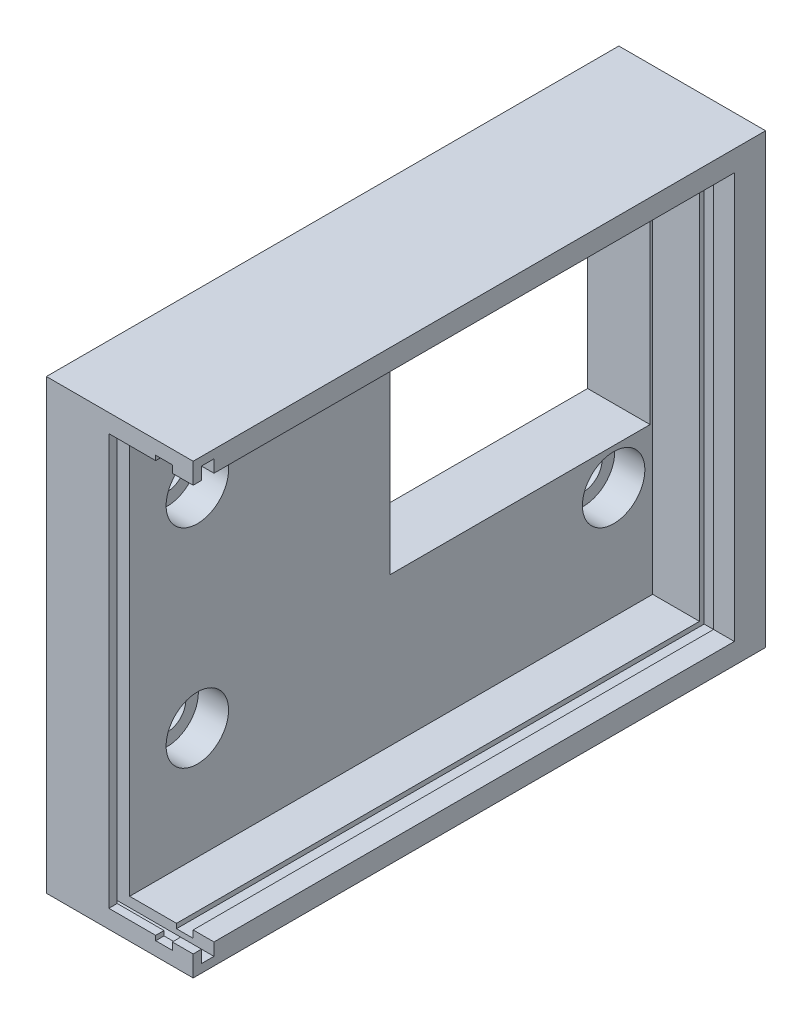
SolidWorks part; units mm, degrees
ref_plane "Front Plane" through (0, 0, 0) normal (1, 0, 0) x (0, 1, 0)
ref_plane "Top Plane" through (0, 0, 0) normal (0, 0, 1) x (0, 1, 0)
ref_plane "Right Plane" through (0, 0, 0) normal (0, 1, 0) x (-1, 0, 0)
sketch "Sketch1" plane through (0, 0, 0) normal (1, 0, 0) x (0, 1, 0)
  line L14 (-11.7365, -20.1625) -> (-11.7365, 19.8375) construction
  line L15 (-24.2365, 28.3375) -> (-24.2365, -26.6625)
  line L16 (-24.2365, 28.3375) -> (18.7635, 28.3375)
  line L17 (-24.2365, -26.6625) -> (18.7635, -26.6625)
  line L18 (18.7635, -26.6625) -> (18.7635, 28.3375)
  circle A0 centre (-11.7365, -20.1625) radius 1.8
  circle A1 centre (-11.7365, 19.8375) radius 1.8
  circle A2 centre (8.2635, 19.8375) radius 1.8
  dimension "D7" = 3.6
  dimension "D8" = 3.6
  dimension "D9" = 3.6
  dimension "D1" = 6.5
  dimension "D2" = 43
  dimension "D3" = 12.5
  dimension "D4" = 40
  dimension "D5" = 55
  dimension "D6" = 20
  dimension "D10" = 46.5
extrude "Boss-Extrude1" add sketch "Sketch1" along normal blind 6
sketch "Sketch3" plane through (6, 0, 0) normal (1, 0, 0) x (0, 1, 0)
  line L0 (-24.2365, 28.3375) -> (18.7635, -26.6625) construction
  line L5 (18.7635, -26.6625) -> (18.7635, 28.3375) construction
  line L6 (18.7635, 28.3375) -> (-24.2365, -26.6625) construction
  line L7 (-22.4865, 25.5875) -> (-22.4865, 28.3375)
  line L15 (-22.4865, 25.5875) -> (-22.4865, -23.9125)
  line L16 (-22.4865, -23.9125) -> (17.0135, -23.9125)
  line L19 (17.0135, 25.5875) -> (17.0135, -23.9125)
  line L20 (-22.4865, 25.5875) -> (17.0135, -23.9125) construction
  line L21 (-22.4865, -23.9125) -> (17.0135, 25.5875) construction
  line L22 (-24.2365, 28.3375) -> (-22.4865, 28.3375)
  line L23 (-24.2365, 28.3375) -> (-24.2365, -26.6625)
  line L24 (-24.2365, -26.6625) -> (18.7635, -26.6625)
  line L25 (18.7635, 28.3375) -> (18.7635, -26.6625)
  line L26 (-24.2365, 28.3375) -> (18.7635, -26.6625) construction
  line L27 (-24.2365, -26.6625) -> (18.7635, 28.3375) construction
  line L28 (17.0135, 25.5875) -> (17.0135, 28.3375)
  line L29 (17.0135, 28.3375) -> (18.7635, 28.3375)
  point P2 (-2.7365, 0.8375)
  point P9 (-2.7365, 0.8375)
  dimension "D1" = 49.5
  dimension "D2" = 39.5
extrude "Boss-Extrude2" add sketch "Sketch3" along normal blind 4.5
sketch "Sketch5" plane through (10.5, 0, 0) normal (1, 0, 0) x (0, 1, 0)
  line L0 (-24.2365, 28.3375) -> (18.7635, -26.6625) construction
  line L1 (18.7635, -26.6625) -> (18.7635, 28.3375) construction
  line L7 (18.7635, 28.3375) -> (-24.2365, -26.6625) construction
  line L8 (-22.9365, 26.0375) -> (-22.9365, 28.3375)
  line L14 (-22.9365, 26.0375) -> (-22.9365, -24.3625)
  line L18 (-22.9365, -24.3625) -> (17.4635, -24.3625)
  line L19 (17.4635, 26.0375) -> (17.4635, -24.3625)
  line L20 (-22.9365, 26.0375) -> (17.4635, -24.3625) construction
  line L21 (-22.9365, -24.3625) -> (17.4635, 26.0375) construction
  line L22 (-24.2365, 28.3375) -> (-22.9365, 28.3375)
  line L23 (-24.2365, 28.3375) -> (-24.2365, -26.6625)
  line L24 (-24.2365, -26.6625) -> (18.7635, -26.6625)
  line L25 (18.7635, 28.3375) -> (18.7635, -26.6625)
  line L26 (-24.2365, 28.3375) -> (18.7635, -26.6625) construction
  line L27 (-24.2365, -26.6625) -> (18.7635, 28.3375) construction
  line L28 (17.4635, 26.0375) -> (17.4635, 28.3375)
  line L29 (17.4635, 28.3375) -> (18.7635, 28.3375)
  point P4 (-2.7365, 0.8375)
  point P13 (-2.7365, 0.8375)
  dimension "D1" = 50.4
  dimension "D2" = 40.4
extrude "Boss-Extrude3" add sketch "Sketch5" along normal blind 1.6 contours L14 L18 L19 L28 L29 L25 L24 L23 L22 L8
sketch "Sketch6" plane through (12.1, 0, 0) normal (1, 0, 0) x (0, 1, 0)
  line L4 (-24.2365, 28.3375) -> (18.7635, -26.6625) construction
  line L5 (18.7635, -26.6625) -> (18.7635, 28.3375) construction
  line L11 (18.7635, 28.3375) -> (-24.2365, -26.6625) construction
  line L12 (-22.2365, 25.3375) -> (-22.2365, 28.3375)
  line L16 (-22.2365, 25.3375) -> (-22.2365, -23.6625)
  line L17 (-22.2365, -23.6625) -> (16.7635, -23.6625)
  line L18 (16.7635, 25.3375) -> (16.7635, -23.6625)
  line L19 (-22.2365, 25.3375) -> (16.7635, -23.6625) construction
  line L20 (-22.2365, -23.6625) -> (16.7635, 25.3375) construction
  line L21 (-24.2365, 28.3375) -> (-22.2365, 28.3375)
  line L22 (-24.2365, 28.3375) -> (-24.2365, -26.6625)
  line L23 (-24.2365, -26.6625) -> (18.7635, -26.6625)
  line L24 (18.7635, 28.3375) -> (18.7635, -26.6625)
  line L25 (-24.2365, 28.3375) -> (18.7635, -26.6625) construction
  line L26 (-24.2365, -26.6625) -> (18.7635, 28.3375) construction
  line L27 (16.7635, 25.3375) -> (16.7635, 28.3375)
  line L28 (16.7635, 28.3375) -> (18.7635, 28.3375)
  point P2 (-2.7365, 0.8375)
  point P11 (-2.7365, 0.8375)
  dimension "D1" = 39
  dimension "D2" = 49
extrude "Boss-Extrude4" add sketch "Sketch6" along normal blind 2
sketch "Sketch7" plane through (14.1, 0, 0) normal (1, 0, 0) x (0, 1, 0)
  circle A0 centre (-11.7365, -20.1625) radius 3
  circle A1 centre (-11.7365, 19.8375) radius 3
  circle A2 centre (8.2635, 19.8375) radius 3
  dimension "D1" = 6
extrude "Cut-Extrude2" cut sketch "Sketch7" against normal blind 11
sketch "Sketch11" plane through (6, 0, 0) normal (1, 0, 0) x (0, 1, 0)
  line L1 (16.7635, -23.6625) -> (-8.2365, -23.6625)
  line L2 (16.7635, -23.6625) -> (16.7635, 1.3375)
  line L3 (16.7635, 1.3375) -> (-8.2365, 1.3375)
  line L4 (-8.2365, -23.6625) -> (-8.2365, 1.3375)
  dimension "D1" = 25
  dimension "D2" = 25
extrude "Cut-Extrude5" cut sketch "Sketch11" against normal blind 11.5
sketch "Sketch17" plane through (14.1, 0, 0) normal (1, 0, 0) x (0, 1, 0)
  line L1 (-23.4365, 27.5375) -> (17.9635, 27.5375)
  line L2 (-23.4365, 27.5375) -> (-23.4365, 26.3375)
  line L3 (-23.4365, 26.3375) -> (17.9635, 26.3375)
  line L4 (17.9635, 27.5375) -> (17.9635, 26.3375)
  line L6 (17.0135, 28.3375) -> (-22.4865, 28.3375) construction
  line L7 (-24.2365, 28.3375) -> (-24.2365, -26.6625) construction
  line L8 (18.7635, -26.6625) -> (18.7635, 28.3375) construction
  dimension "D1" = 0.8
  dimension "D2" = 1.2
  dimension "D3" = 0.8
  dimension "D4" = 0.8
extrude "Cut-Extrude7" cut sketch "Sketch17" against normal blind 11
